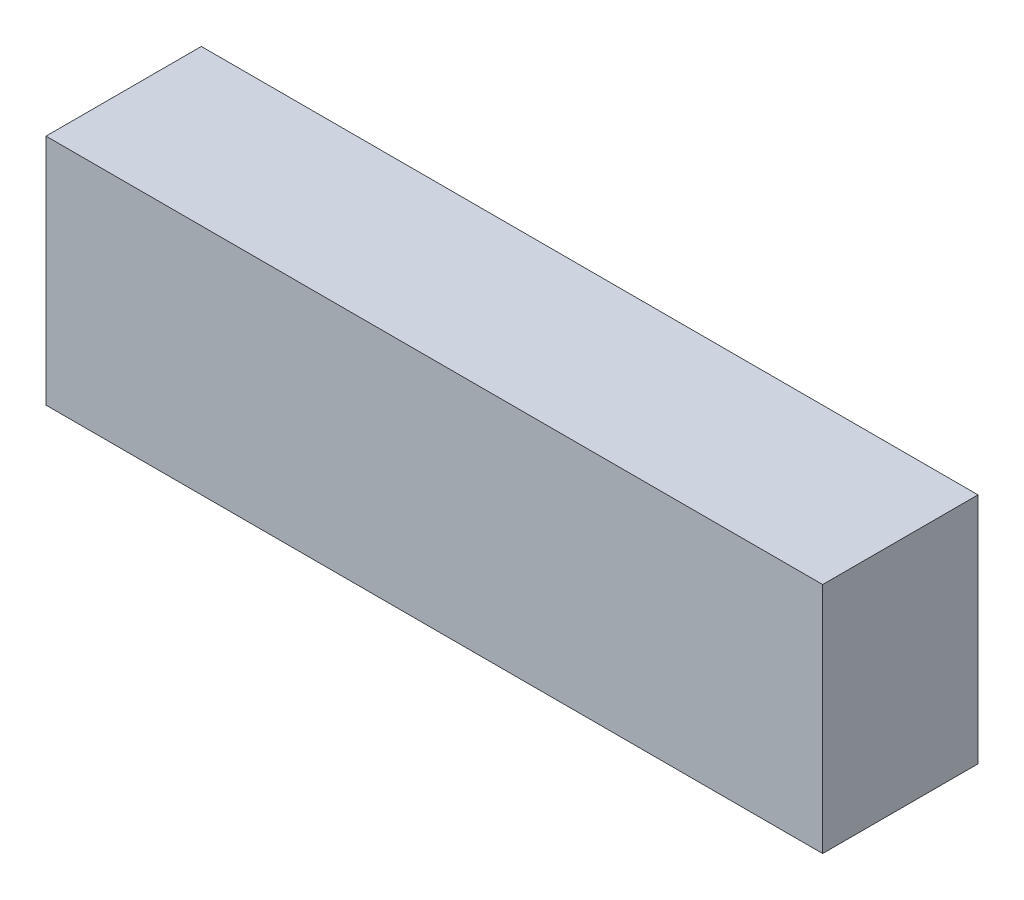
SolidWorks part; units mm, degrees
ref_plane "前视基准面" through (0, 0, 0) normal (0, 0, 1) x (1, 0, 0)
ref_plane "上视基准面" through (0, 0, 0) normal (0, 1, 0) x (1, 0, 0)
ref_plane "右视基准面" through (0, 0, 0) normal (1, 0, 0) x (0, 0, -1)
other "Configuration Table"
sketch "草图1" plane through (0, 0, 0) normal (0, 0, 1) x (1, 0, 0)
  line L1 (-30, -9) -> (30, -9)
  line L2 (-30, -9) -> (-30, 9)
  line L3 (-30, 9) -> (30, 9)
  line L4 (30, -9) -> (30, 9)
  line L5 (-30, -9) -> (30, 9) construction
  line L6 (-30, 9) -> (30, -9) construction
  point P0 (0, 0)
extrude "凸台-拉伸1" add sketch "草图1" along normal blind 12
